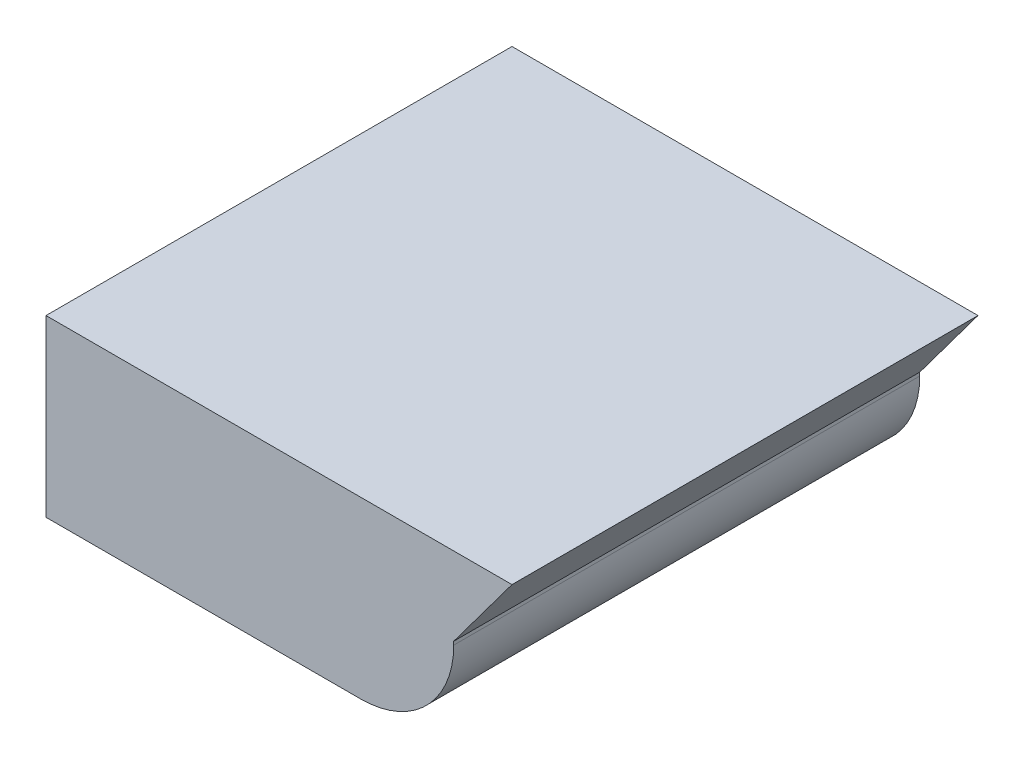
SolidWorks part; units mm, degrees
ref_plane "Front Plane" through (0, 0, 0) normal (0, 0, 1) x (1, 0, 0)
ref_plane "Top Plane" through (0, 0, 0) normal (0, 1, 0) x (1, 0, 0)
ref_plane "Right Plane" through (0, 0, 0) normal (1, 0, 0) x (0, 0, -1)
sketch "Sketch1" plane through (0, 0, 0) normal (0, 0, 1) x (1, 0, 0)
  line L0 (-13.7681, -75.8661) -> (26.2319, -75.8661)
  line L1 (26.2319, -75.8661) -> (21.2319, -82.5752)
  line L2 (21.2319, -82.5752) -> (21.2319, -90.8661)
  line L3 (21.2319, -90.8661) -> (-13.7681, -90.8661)
  line L4 (-13.7681, -90.8661) -> (-13.7681, -75.8661)
  dimension "D1" = 35
  dimension "D2" = 15
  dimension "D3" = 40
extrude "Boss-Extrude1" add sketch "Sketch1" along normal blind 40
fillet "Fillet1" radius 8 1 edges at (21.2319, -90.8661, 20)
